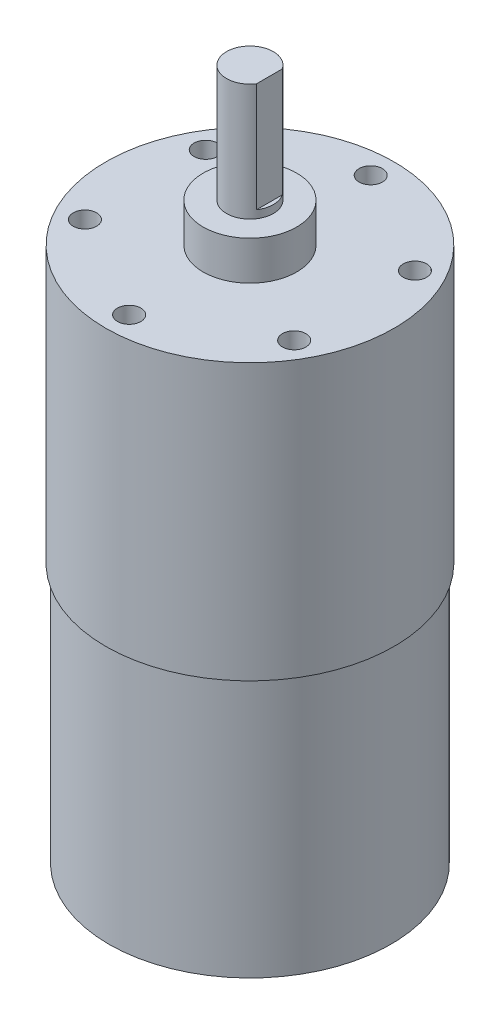
SolidWorks part; units mm, degrees
ref_plane "Front Plane" through (0, 0, 0) normal (0, 0, 1) x (1, 0, 0)
ref_plane "Top Plane" through (0, 0, 0) normal (0, 1, 0) x (1, 0, 0)
ref_plane "Right Plane" through (0, 0, 0) normal (1, 0, 0) x (0, 0, -1)
sketch "Sketch1" plane through (0, 0, 0) normal (0, 1, 0) x (1, 0, 0)
  circle A0 centre (0, 0) radius 18.1
  dimension "D1" = 36.2
extrude "Boss-Extrude1" add sketch "Sketch1" along normal blind 33.3
sketch "Sketch2" plane through (0, 33.3, 0) normal (0, 1, 0) x (1, 0, 0)
  circle A0 centre (0, 0) radius 18.5
  dimension "D1" = 37
extrude "Boss-Extrude2" add sketch "Sketch2" along normal blind 35.3568
sketch "Sketch3" plane through (0, 68.6568, 0) normal (0, 1, 0) x (1, 0, 0)
  circle A0 centre (0, 0) radius 6
  dimension "D1" = 12
extrude "Boss-Extrude3" add sketch "Sketch3" along normal blind 5
sketch "Sketch4" plane through (0, 73.6568, 0) normal (0, 1, 0) x (1, 0, 0)
  circle A0 centre (0, 0) radius 3
  dimension "D1" = 6
extrude "Boss-Extrude4" add sketch "Sketch4" along normal blind 15
sketch "Sketch5" plane through (0, 0, 0) normal (0, 0, 1) x (1, 0, 0)
  line L1 (3, 88.6568) -> (2.5, 88.6568)
  line L2 (3, 88.6568) -> (3, 74.6568)
  line L3 (3, 74.6568) -> (2.5, 74.6568)
  line L4 (2.5, 88.6568) -> (2.5, 74.6568)
  dimension "D1" = 0.5
  dimension "D2" = 14
extrude "Cut-Extrude1" cut sketch "Sketch5" against normal through all and the other way through all
sketch "Sketch6" plane through (0, 68.6568, 0) normal (0, 1, 0) x (1, 0, 0)
  circle A0 centre (0, 15.5) radius 1.5
  point P2 (0, 0)
  dimension "D2" = 3
  dimension "D1" = 15.5
extrude "Cut-Extrude2" cut sketch "Sketch6" against normal blind 10
pattern_circular "CirPattern1" count 6 over 360 about axis through (0, 0, 0) along (0, 1, 0) of "Cut-Extrude2"
